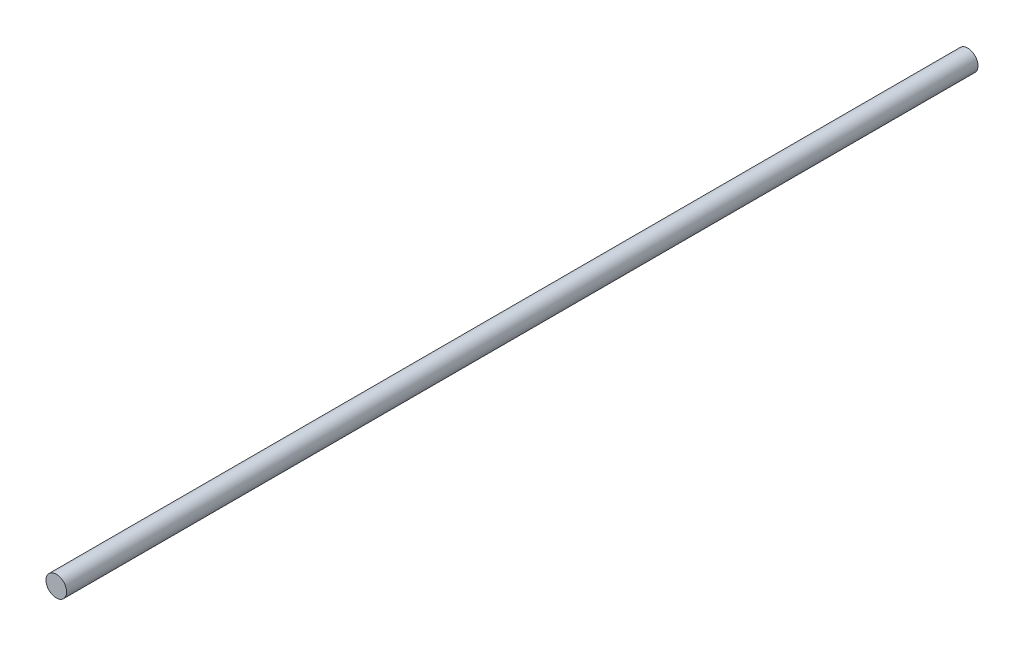
SolidWorks part; units mm, degrees
ref_plane "Alzado" through (0, 0, 0) normal (0, 0, 1) x (1, 0, 0)
ref_plane "Planta" through (0, 0, 0) normal (0, 1, 0) x (1, 0, 0)
ref_plane "Vista lateral" through (0, 0, 0) normal (1, 0, 0) x (0, 0, -1)
sketch "Croquis1" plane through (0, 0, 0) normal (0, 0, 1) x (1, 0, 0)
  circle A0 centre (0, 0) radius 4
  dimension "D1" = 8
extrude "Saliente-Extruir1" add sketch "Croquis1" along normal mid plane 354
